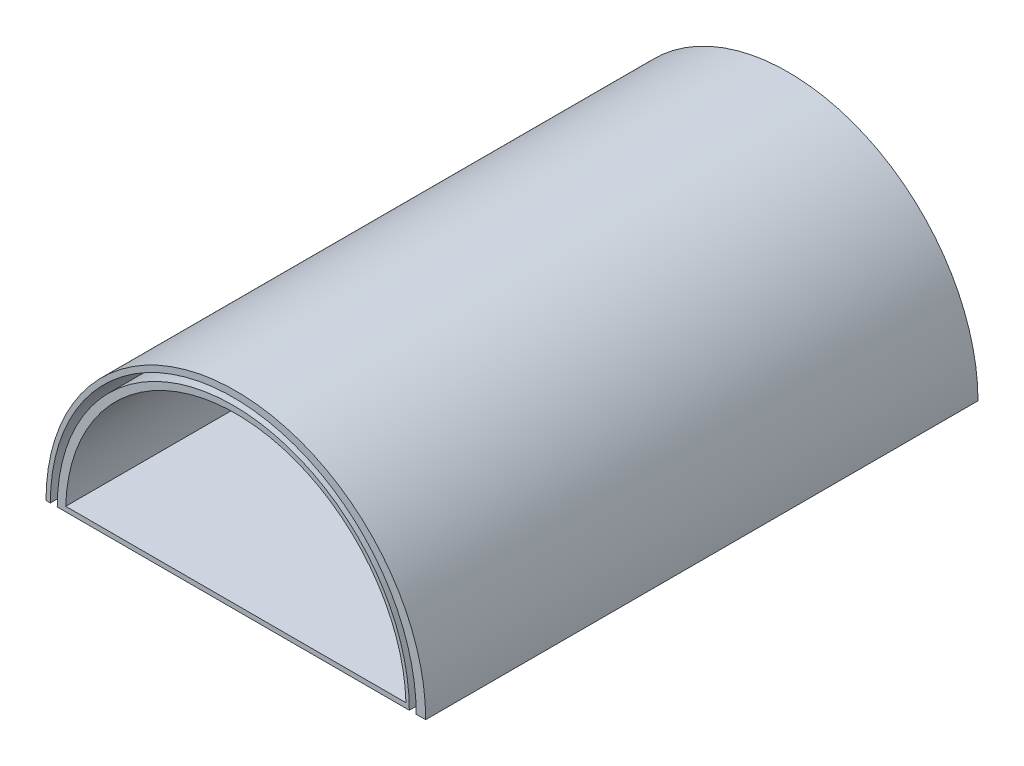
SolidWorks part; units mm, degrees
ref_plane "Front" through (0, 0, 0) normal (0, 0, 1) x (1, 0, 0)
ref_plane "Top" through (0, 0, 0) normal (0, 1, 0) x (1, 0, 0)
ref_plane "Right" through (0, 0, 0) normal (1, 0, 0) x (0, 0, -1)
sketch "Sketch2" plane through (0, 0, 0) normal (0, 0, 1) x (1, 0, 0)
  line L0 (-69.85, 0) -> (69.85, 0)
  arc A0 (69.85, 0) -> (-69.85, 0) centre (0, 0) ccw
  dimension "D1" = 139.7
extrude "Boss-Extrude1" add sketch "Sketch2" along normal blind 203.2
sketch "Sketch3" plane through (0, 0, 203.2) normal (0, 0, 1) x (1, 0, 0)
  line L0 (-69.85, 0) -> (69.85, 0) construction
  line L1 (-62.5857, 1.778) -> (62.5857, 1.778)
  arc A0 (62.5857, 1.778) -> (-62.5857, 1.778) centre (0, 0) ccw
  dimension "D1" = 125.222
  dimension "D2" = 1.778
extrude "Cut-Extrude1" cut sketch "Sketch3" against normal blind 201.422
sketch "Sketch5" plane through (0, 0, 203.2) normal (0, 0, 1) x (1, 0, 0)
  line L0 (-69.85, 0) -> (69.85, 0) construction
  line L1 (66.3633, 0) -> (63.8233, 0)
  line L2 (-65.7167, 0) -> (-68.2567, 0)
  arc A0 (-68.2567, 0) -> (66.3633, 0) centre (-0.9467, 0) cw
  arc A1 (-65.7167, 0) -> (63.8233, 0) centre (-0.9467, 0) cw
  point P8 (-0.9467, 64.77)
  point P10 (-0.9467, 67.31)
  dimension "D1" = 64.77
  dimension "D2" = 67.31
extrude "Cut-Extrude2" cut sketch "Sketch5" against normal blind 101.6
